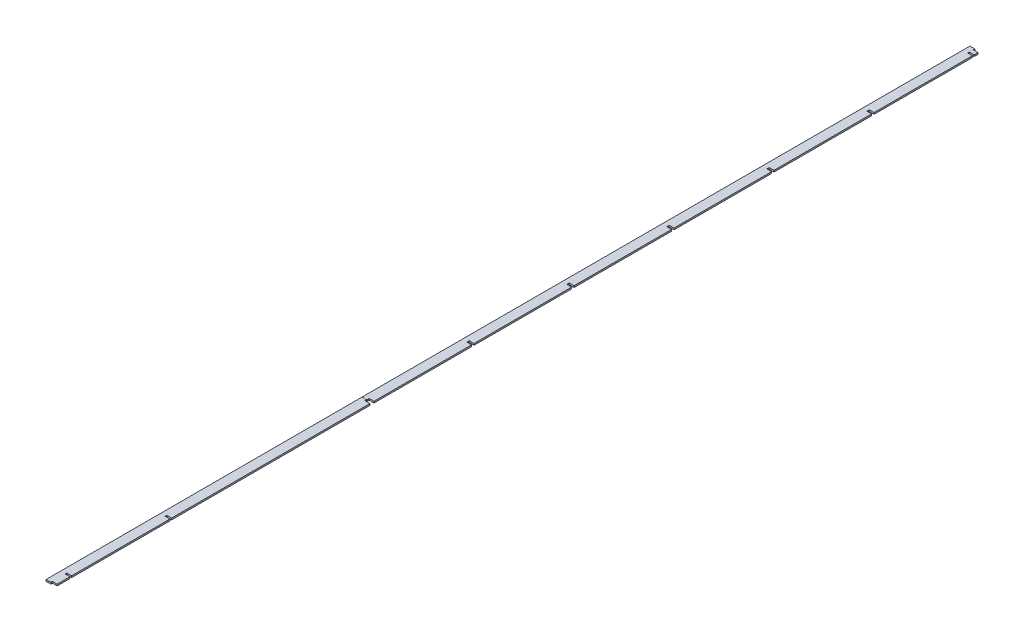
SolidWorks part; units mm, degrees
material "轻木"
ref_plane "前视基准面" through (0, 0, 0) normal (0, 0, 1) x (1, 0, 0)
ref_plane "上视基准面" through (0, 0, 0) normal (0, 1, 0) x (1, 0, 0)
ref_plane "右视基准面" through (0, 0, 0) normal (1, 0, 0) x (0, 0, -1)
other "Configuration Table"
sketch "草图1" plane through (0, 0, 0) normal (0, 0, 1) x (1, 0, 0)
  line L0 (-137.1255, -1006.8019) -> (-137.1255, 48993.1981) construction
  line L1 (-136.0466, -5.3019) -> (-131.1255, -5.3019) construction
  line L2 (-137.1255, -5.3019) -> (-125.1255, -5.3019)
  line L3 (-137.1255, -5.3019) -> (-137.1255, -7.3019)
  line L4 (-137.1255, -7.3019) -> (-125.1255, -7.3019)
  line L5 (-125.1255, -5.3019) -> (-125.1255, -7.3019)
  dimension "D1" = 12
  dimension "D2" = 2
extrude "凸台-拉伸1" add sketch "草图1" along normal blind 1155
sketch "草图3" plane through (0, -5.3019, 0) normal (0, 1, 0) x (1, 0, 0)
  line L0 (-125.1255, -1155) -> (-125.1255, 0) construction
  line L1 (-125.1255, 0) -> (-131.1255, 0)
  line L2 (-125.1255, 0) -> (-125.1255, -2)
  line L3 (-125.1255, -2) -> (-131.1255, -2)
  line L4 (-131.1255, 0) -> (-131.1255, -2)
  line L34 (-125.1255, -9) -> (-131.1255, -9)
  line L53 (-131.1255, -885) -> (-125.1255, -885)
  line L65 (-125.1255, -9) -> (-125.1255, -7)
  line L66 (-125.1255, -7) -> (-131.1255, -7)
  line L67 (-131.1255, -9) -> (-131.1255, -7)
  line L111 (-125.1255, -257) -> (-125.1255, -260)
  line L124 (-131.1255, -257) -> (-131.1255, -260)
  line L144 (-131.1255, -260) -> (-125.1255, -260)
  line L145 (-131.1255, -132) -> (-125.1255, -132)
  line L146 (-131.1255, -132) -> (-131.1255, -135)
  line L147 (-131.1255, -135) -> (-125.1255, -135)
  line L148 (-125.1255, -132) -> (-125.1255, -135)
  line L149 (-131.1255, -257) -> (-125.1255, -257)
  line L150 (-125.1255, -382) -> (-125.1255, -385)
  line L151 (-131.1255, -382) -> (-131.1255, -385)
  line L152 (-131.1255, -385) -> (-125.1255, -385)
  line L153 (-131.1255, -382) -> (-125.1255, -382)
  line L154 (-125.1255, -507) -> (-125.1255, -510)
  line L155 (-131.1255, -507) -> (-131.1255, -510)
  line L156 (-131.1255, -510) -> (-125.1255, -510)
  line L157 (-131.1255, -507) -> (-125.1255, -507)
  line L158 (-125.1255, -632) -> (-125.1255, -635)
  line L159 (-131.1255, -632) -> (-131.1255, -635)
  line L160 (-131.1255, -635) -> (-125.1255, -635)
  line L161 (-131.1255, -632) -> (-125.1255, -632)
  line L162 (-125.1255, -757) -> (-125.1255, -760)
  line L163 (-131.1255, -757) -> (-131.1255, -760)
  line L164 (-131.1255, -760) -> (-125.1255, -760)
  line L165 (-131.1255, -757) -> (-125.1255, -757)
  line L166 (-125.1255, -132) -> (-125.1255, -257) construction
  line L167 (-131.1255, -885) -> (-131.1255, -887)
  line L168 (-125.1255, -760) -> (-131.1255, -760)
  line L169 (-125.1255, -760) -> (-125.1255, -762)
  line L170 (-125.1255, -762) -> (-131.1255, -762)
  line L171 (-131.1255, -760) -> (-131.1255, -762)
  line L172 (-125.1255, -887) -> (-131.1255, -887)
  line L173 (-125.1255, -885) -> (-125.1255, -887)
  line L174 (-131.1255, -1010) -> (-125.1255, -1010)
  line L175 (-131.1255, -1010) -> (-131.1255, -1012)
  line L176 (-125.1255, -1012) -> (-131.1255, -1012)
  line L177 (-125.1255, -1010) -> (-125.1255, -1012)
  line L178 (-131.1255, -1135) -> (-125.1255, -1135)
  line L179 (-131.1255, -1135) -> (-131.1255, -1137)
  line L180 (-125.1255, -1137) -> (-131.1255, -1137)
  line L181 (-125.1255, -1135) -> (-125.1255, -1137)
  line L182 (-131.1255, -760) -> (-131.1255, -885) construction
  line L183 (-137.1255, -1155) -> (-137.1255, 0) construction
  line L184 (-125.1255, -1155) -> (-131.1255, -1155)
  line L185 (-125.1255, -1155) -> (-125.1255, -1153)
  line L186 (-125.1255, -1153) -> (-131.1255, -1153)
  line L187 (-131.1255, -1155) -> (-131.1255, -1153)
  line L188 (-131.1255, -759.9) -> (-137.1255, -759.9)
  line L189 (-131.1255, -759.9) -> (-131.1255, -760.1)
  line L190 (-131.1255, -760.1) -> (-137.1255, -760.1)
  line L191 (-137.1255, -759.9) -> (-137.1255, -760.1)
  line M3 (-125.1255, 0) -> (-137.1255, 0)
  line M4 (-137.1255, 0) -> (-137.1255, -1155)
  line M5 (-137.1255, -1155) -> (-125.1255, -1155)
  line M6 (-125.1255, -1155) -> (-125.1255, 0)
  dimension "D3" = 125
  dimension "D2" = 6
  dimension "D5" = 7
  dimension "D6" = 2
  dimension "D7" = 6
  dimension "D8" = 2
  dimension "D9" = 4
  dimension "D10" = 125
  dimension "D11" = 125
  dimension "D12" = 6
  dimension "D13" = 2
  dimension "D14" = 0.2
  dimension "D15" = 0.1
  dimension "D16" = 2
  dimension "D17" = 6
  dimension "D4" = 3
extrude "切除-拉伸1" cut sketch "草图3" against normal through all contours L187 L186 M5 M6 | L180 L178 L179 M6 | L176 L174 L175 M6 | L165 L163 L164 M6 | L164 L171 L170 M6 | L161 L159 L160 M6 | L157 L155 L156 M6 | L153 L151 L152 M6 | L149 L124 L144 M6 | L146 L147 L145 M6 | L67 L34 L66 M6 | L4 L3 M3 M6 | L190 L171 L163 L188 M4 | L53 L173 L172 L167
